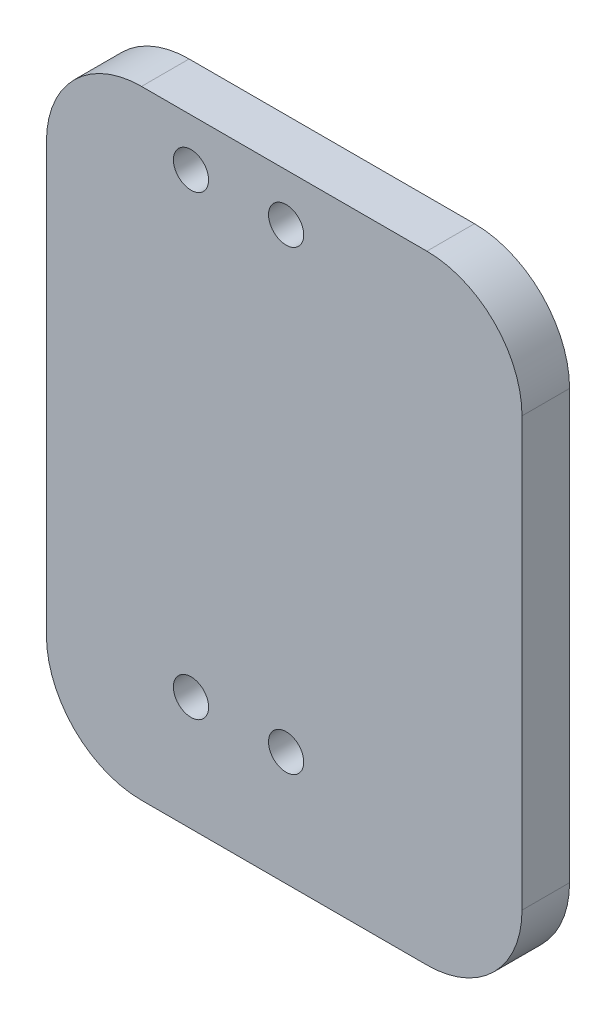
SolidWorks part; units mm, degrees
ref_plane "Plan de face" through (0, 0, 0) normal (0, 0, 1) x (1, 0, 0)
ref_plane "Plan de dessus" through (0, 0, 0) normal (0, 1, 0) x (1, 0, 0)
ref_plane "Plan de droite" through (0, 0, 0) normal (1, 0, 0) x (0, 0, -1)
sketch "Esquisse1" plane through (0, 0, 0) normal (0, 0, 1) x (1, 0, 0)
  line L1 (-25, 32.5) -> (25, 32.5)
  line L2 (-25, 32.5) -> (-25, -32.5)
  line L3 (-25, -32.5) -> (25, -32.5)
  line L4 (25, 32.5) -> (25, -32.5)
  line L5 (-25, 32.5) -> (25, -32.5) construction
  line L6 (-25, -32.5) -> (25, 32.5) construction
  point P0 (0, 0)
  dimension "D1" = 50
  dimension "D2" = 65
extrude "Boss.-Extru.1" add sketch "Esquisse1" along normal blind 5
sketch "Esquisse2" plane through (0, 0, 5) normal (0, 0, 1) x (1, 0, 0)
  circle A0 centre (-9.8, -20.5) radius 1.85
  circle A1 centre (0.2, -20.5) radius 1.85
  circle A2 centre (-9.8, 27.5) radius 1.85
  circle A3 centre (0.2, 27.5) radius 1.85
extrude "Enlèv. mat.-Extru.1" cut sketch "Esquisse2" against normal through all
fillet "Congé1" radius 10 4 edges at (25, 32.5, 2.5) (-25, 32.5, 2.5) (25, -32.5, 2.5) (-25, -32.5, 2.5)
